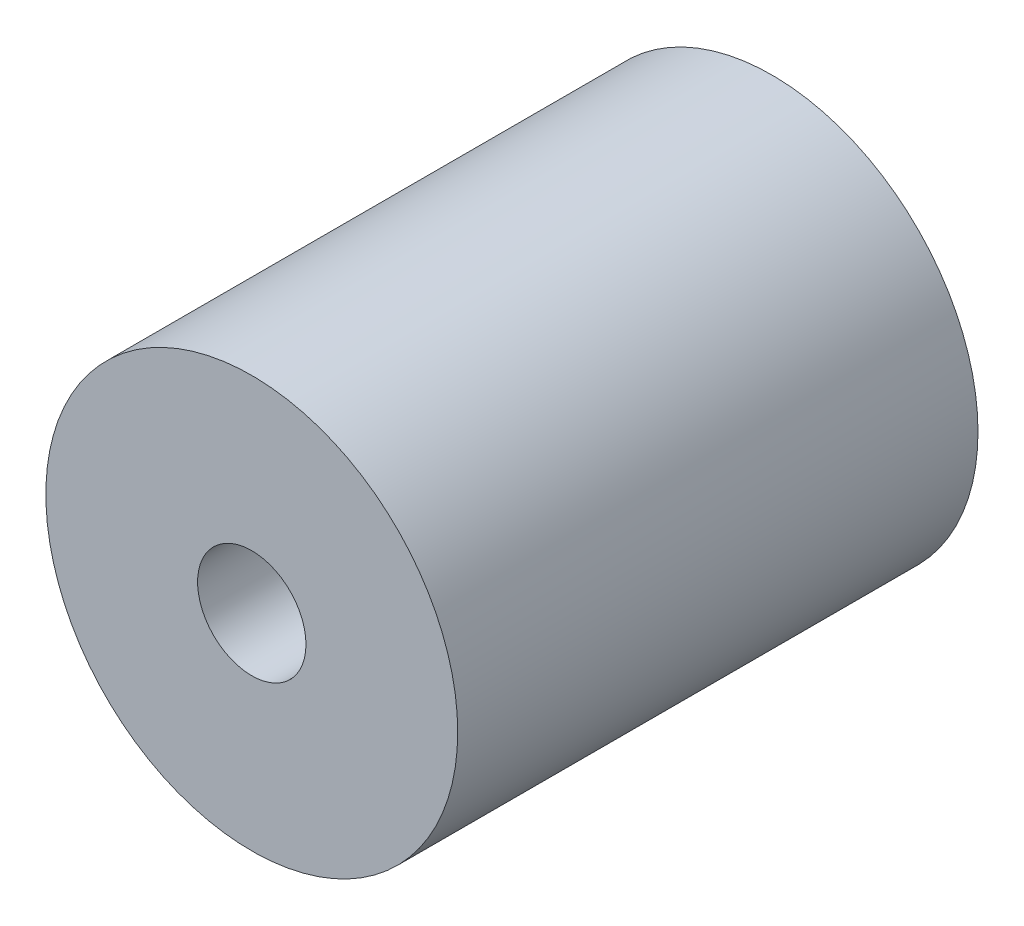
SolidWorks part; units mm, degrees
ref_plane "前基準面" through (0, 0, 0) normal (0, 0, 1) x (1, 0, 0)
ref_plane "上基準面" through (0, 0, 0) normal (0, 1, 0) x (1, 0, 0)
ref_plane "右基準面" through (0, 0, 0) normal (1, 0, 0) x (0, 0, -1)
sketch "草圖1" plane through (0, 0, 0) normal (0, 0, 1) x (1, 0, 0)
  circle A0 centre (0, 0) radius 9.5
  circle A1 centre (0, 0) radius 4
  dimension "D1" = 19
  dimension "D2" = 8
extrude "填料-伸長1" add sketch "草圖1" along normal blind 24
sketch "草圖2" plane through (0, 0, 24) normal (0, 0, 1) x (1, 0, 0)
  circle A0 centre (0, 0) radius 4
  circle A1 centre (0, 0) radius 2.5
  dimension "D1" = 5
extrude "填料-伸長2" add sketch "草圖2" against normal blind 12
